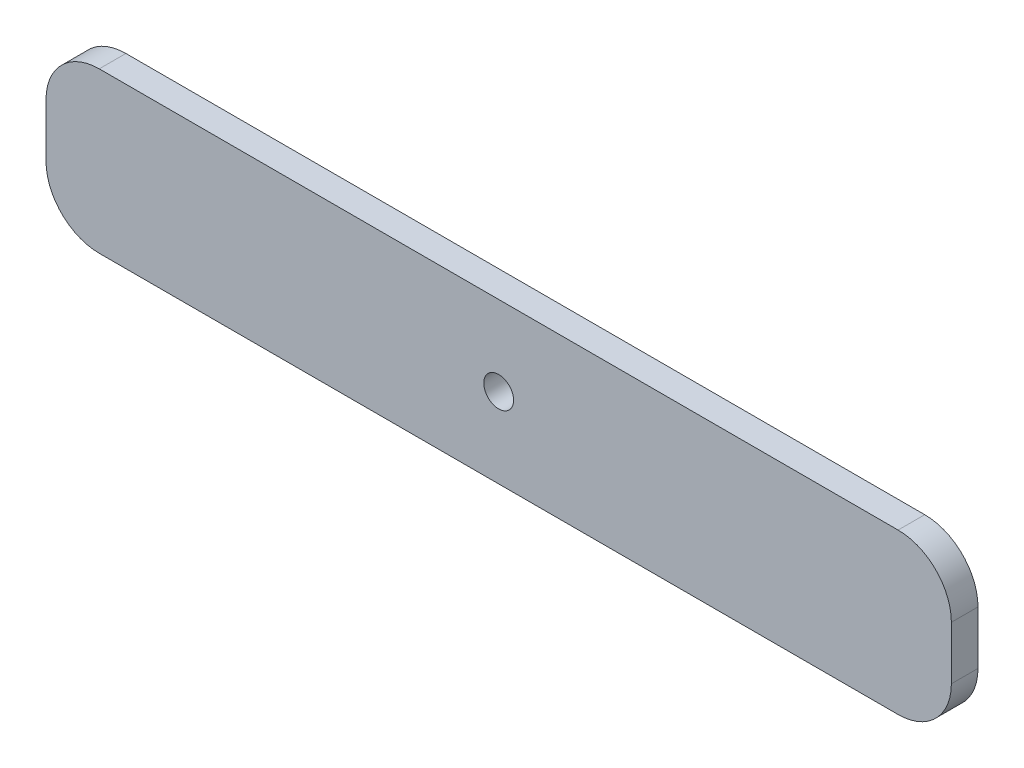
SolidWorks part; units mm, degrees
ref_plane "Plan de face" through (0, 0, 0) normal (0, 0, 1) x (1, 0, 0)
ref_plane "Plan de dessus" through (0, 0, 0) normal (0, 1, 0) x (1, 0, 0)
ref_plane "Plan de droite" through (0, 0, 0) normal (1, 0, 0) x (0, 0, -1)
sketch "Esquisse1" plane through (0, 0, 0) normal (0, 0, 1) x (1, 0, 0)
  line L0 (10, -10) -> (160, -20) construction
  line L1 (10, 0) -> (160, 0)
  line L2 (0, -10) -> (0, -20)
  line L3 (10, -30) -> (160, -30)
  line L4 (170, -10) -> (170, -20)
  line L5 (10, -20) -> (160, -10) construction
  arc A0 (0, -20) -> (10, -30) centre (10, -20) ccw
  arc A1 (160, -30) -> (170, -20) centre (160, -20) ccw
  arc A2 (170, -10) -> (160, 0) centre (160, -10) ccw
  arc A3 (0, -10) -> (10, 0) centre (10, -10) cw
  circle A4 centre (85, -15) radius 2.8
  point P13 (0, 0)
  dimension "D1" = 10
  dimension "D3" = 30
  dimension "D4" = 5.6
  dimension "D2" = 150
extrude "Boss.-Extru.1" add sketch "Esquisse1" along normal blind 5
